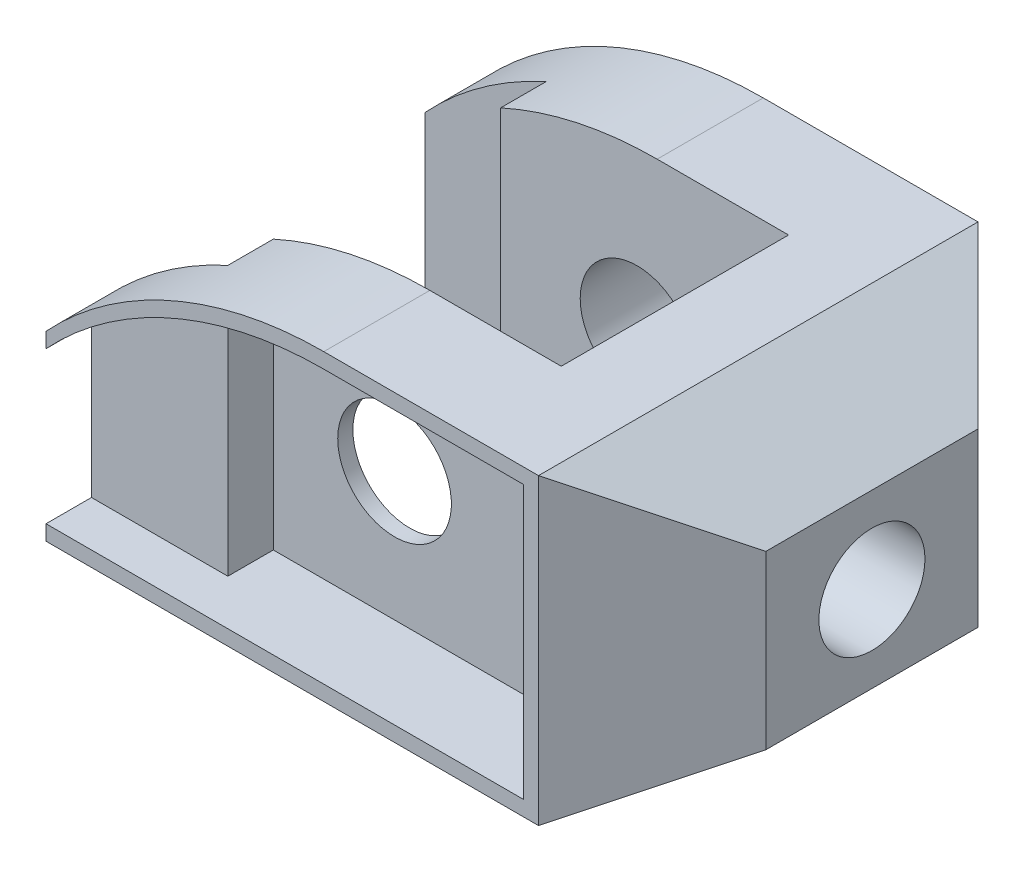
SolidWorks part; units mm, degrees
material "1060 Alloy"
ref_plane "Front Plane" through (0, 0, 0) normal (0, 0, 1) x (1, 0, 0)
ref_plane "Top Plane" through (0, 0, 0) normal (0, 1, 0) x (1, 0, 0)
ref_plane "Right Plane" through (0, 0, 0) normal (1, 0, 0) x (0, 0, -1)
sketch "Sketch1" plane through (0, 0, 0) normal (0, 0, 1) x (1, 0, 0)
  line L0 (0, 0) -> (0, 24)
  line L1 (0, 0) -> (65, 0)
  line L2 (65, 0) -> (80, 8.6603)
  line L3 (80, 8.6603) -> (80, 31.3397)
  line L4 (80, 31.3397) -> (65, 40)
  line L5 (65, 40) -> (36.6606, 40)
  arc A0 (0, 24) -> (36.6606, 40) centre (36.6606, -10) cw
  circle A1 centre (34, 19) radius 7.5
  dimension "D6" = 50
  dimension "D8" = 15
  dimension "D1" = 65
  dimension "D2" = 15
  dimension "D3" = 30
  dimension "D4" = 40
  dimension "D5" = 30
  dimension "D7" = 24
  dimension "D9" = 31
  dimension "D10" = 19
extrude "Boss-Extrude1" add sketch "Sketch1" along normal blind 58
sketch "Sketch2" plane through (0, 0, 0) normal (0, -1, 0) x (-1, 0, 0)
  line L0 (0, -50) -> (0, -8)
  line L1 (0, -58) -> (0, 0) construction
  line L2 (0, -8) -> (-16, -8)
  line L3 (-16, -8) -> (-16, -14)
  line L4 (-16, -14) -> (-54, -14)
  line L5 (-54, -14) -> (-54, -44)
  line L6 (-54, -44) -> (-16, -44)
  line L7 (-16, -44) -> (-16, -50)
  line L8 (-16, -50) -> (0, -50)
  line L9 (-65, -58) -> (-80, -43)
  line L10 (-80, -58) -> (-80, 0) construction
  line L11 (-80, -43) -> (-80, -58)
  line L12 (-80, -58) -> (-65, -58)
  line L13 (-65, 0) -> (-80, -15)
  line L14 (-80, -15) -> (-80, 0)
  line L15 (-80, 0) -> (-65, 0)
  line L16 (0, -58) -> (-65, -58) construction
  line L17 (0, 0) -> (-65, 0) construction
  line L18 (-65, -58) -> (-65, 0) construction
  line L19 (0, -29) -> (-80, -29) construction
  dimension "D1" = 16
  dimension "D2" = 6
  dimension "D3" = 6
  dimension "D4" = 16
  dimension "D5" = 8
  dimension "D6" = 8
  dimension "D7" = 11
  dimension "D8" = 45
  dimension "D9" = 45
  dimension "D10" = 14
extrude "Cut-Extrude2" cut sketch "Sketch2" against normal blind 58
sketch "Sketch3" plane through (80, 0, 0) normal (1, 0, 0) x (0, 0, -1)
  line L0 (-58, 0) -> (0, 0) construction
  line L1 (-58, 40) -> (-58, 0) construction
  circle A0 centre (-29, 20) radius 7
  dimension "D1" = 14
  dimension "D2" = 20
  dimension "D3" = 29
extrude "Cut-Extrude3" cut sketch "Sketch3" against normal blind 58
sketch "Sketch4" plane through (0, 0, 58) normal (0, 0, 1) x (1, 0, 0)
  line L0 (0, 22) -> (0, 2)
  line L1 (0, 24) -> (0, 0) construction
  line L2 (0, 2) -> (63, 2)
  line L3 (63, 2) -> (63, 38)
  line L4 (63, 38) -> (36.6606, 38)
  line L5 (65, 40) -> (65, 0) construction
  line L6 (0, 0) -> (65, 0) construction
  line L7 (65, 40) -> (36.6606, 40) construction
  arc A0 (0, 22) -> (36.6606, 38) centre (36.6606, -12) cw
  point P8 (41.1751, 37.6841)
  point P10 (0.9854, 21.8398)
  dimension "D1" = 50
  dimension "D2" = 2
  dimension "D3" = 2
  dimension "D4" = 2
  dimension "D5" = 2
extrude "Cut-Extrude5" cut sketch "Sketch4" against normal blind 6
sketch "Sketch6" plane through (0, 0, 52) normal (0, 0, 1) x (1, 0, 0)
  line L0 (63, 38) -> (63, 2)
  line L1 (63, 2) -> (18, 2)
  line L2 (0, 2) -> (63, 2) construction
  line L3 (63, 38) -> (36.6606, 38)
  line L4 (63, 38) -> (36.6606, 38) construction
  line L5 (18, 2) -> (18, 34.3873)
  arc A0 (18, 34.3873) -> (36.6606, 38) centre (36.6606, -12) cw
  arc A1 (36.6606, 38) -> (0, 22) centre (36.6606, -12) ccw construction
  point P12 (16, 33.5317)
  point P13 (16.7016, 27.085)
  point P14 (37.7939, 38.7073)
  point P18 (16, 33.5317)
  point P19 (16, 33.5317)
  point P20 (38.5513, 38)
  dimension "D2" = 50
  dimension "D1" = 45
extrude "Cut-Extrude7" cut sketch "Sketch6" against normal blind 6
equation "\"A\"= 58"
equation "\"B\"= 40"
equation "\"C\"= 65"
equation "\"D1@Sketch1\"=\"C\""
equation "\"D4@Sketch1\"=\"B\""
equation "\"D1@Boss-Extrude1\"=\"A\""
equation "\"D2@Sketch3\"=\"B\"/2"
equation "\"D3@Sketch3\"=\"A\"/2"
equation "\"D1@Sketch6\"=\"C\"-16-4"
